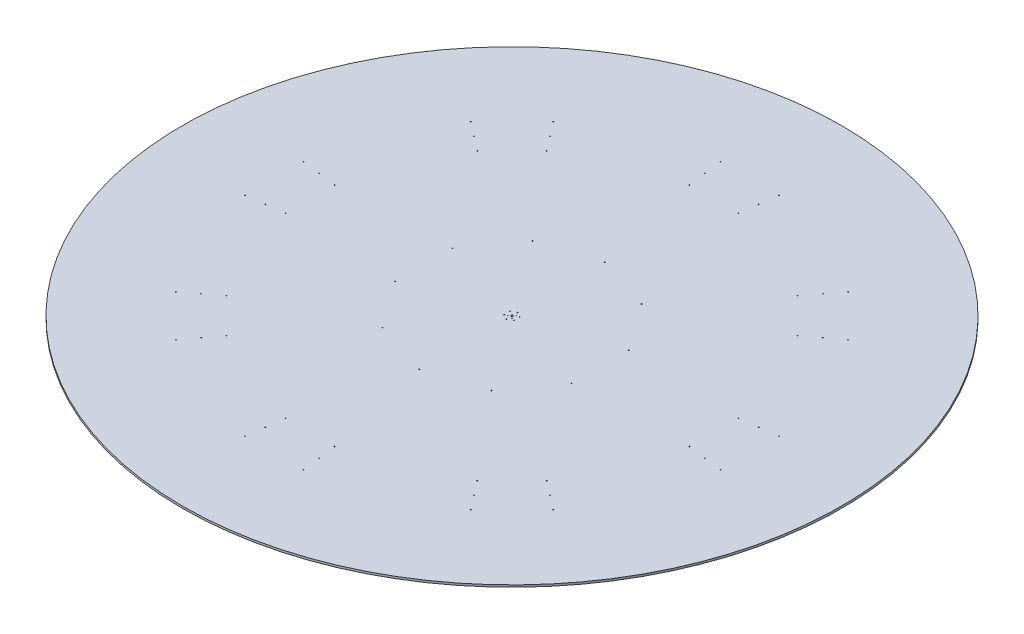
SolidWorks part; units mm, degrees
material "1060 Сплав"
ref_plane "Спереди" through (0, 0, 0) normal (0, 0, 1) x (1, 0, 0)
ref_plane "Сверху" through (0, 0, 0) normal (0, 1, 0) x (1, 0, 0)
ref_plane "Справа" through (0, 0, 0) normal (1, 0, 0) x (0, 0, -1)
sketch "Эскиз1" plane through (0, 0, 0) normal (1, 0, 0) x (0, 0, -1)
  line L0 (1600, 10) -> (5, 10)
  line L1 (1600, 0) -> (1600, 10)
  line L2 (1600, 0) -> (5, 0)
  line L3 (5, 0) -> (5, 10)
  line L4 (0, 18.0501) -> (0, -14.773) construction
  dimension "D1" = 5
  dimension "D2" = 1600
  dimension "D3" = 10
revolve "Повернуть1" add sketch "Эскиз1" angle 360 about L4
sketch "Эскиз2" plane through (0, 0, 0) normal (0, -1, 0) x (1, 0, 0)
  line L0 (0, 1753.4209) -> (0, -1955.8348) construction
  line L1 (-264.5034, 364.0576) -> (264.5034, -364.0576) construction
  line L2 (0, 450) -> (0, -450) construction
  line L3 (-427.9754, 139.0576) -> (427.9754, -139.0576) construction
  line L4 (-427.9754, -139.0576) -> (427.9754, 139.0576) construction
  line L5 (-264.5034, -364.0576) -> (264.5034, 364.0576) construction
  line L6 (23.8157, 13.75) -> (-23.8157, -13.75) construction
  line L7 (23.8157, -13.75) -> (-23.8157, 13.75) construction
  line L8 (0, -27.5) -> (0, 27.5) construction
  circle A0 centre (0, 0) radius 450 construction
  point P1 (-264.5034, 364.0576)
  point P4 (264.5034, 364.0576)
  point P5 (427.9754, 139.0576)
  point P6 (427.9754, -139.0576)
  point P7 (0, -450)
  point P8 (264.5034, -364.0576)
  point P9 (-264.5034, -364.0576)
  point P10 (-427.9754, -139.0576)
  point P11 (-427.9754, 139.0576)
  point P12 (0, 450)
  point P29 (0, 0)
  point P30 (0, 0)
  point P32 (0, 0)
  point P33 (0, 0)
  point P35 (0, 0)
  dimension "D6" = 900
  dimension "D1" = 0
  dimension "D2" = 36
  dimension "D3" = 36
  dimension "D4" = 36
  dimension "D5" = 36
  dimension "D7" = 55
  dimension "D8" = 55
  dimension "D9" = 60
  dimension "D10" = 60
  dimension "D11" = 55
hole_wizard "Отверстие обработанное метчиком M51" positions "Трехмерный эскиз1" profile "Эскиз3" tap size "M5" standard "ISO" end condition through all
sketch3d "Трехмерный эскиз1"
  point P0 (0, 0, 450)
  point P3 (264.5034, 0, 364.0576)
  point P6 (427.9754, 0, 139.0576)
  point P9 (427.9754, 0, -139.0576)
  point P12 (264.5034, 0, -364.0576)
  point P15 (0, 0, -450)
  point P18 (-264.5034, 0, -364.0576)
  point P21 (-427.9754, 0, -139.0576)
  point P24 (-427.9754, 0, 139.0576)
  point P27 (-264.5034, 0, 364.0576)
sketch "Эскиз3" plane through (0, 0, 450) normal (1, 0, 0) x (0, 0, -1)
  line L0 (0, 0) -> (0, 10)
  line L1 (0, 10) -> (2.1, 10)
  line L2 (2.1, 10) -> (2.1, 0)
  line L5 (2.1, 0) -> (0, 0)
  line L11 (0, -6.35) -> (0, 107.95) construction
  dimension "Диаметр проходного сверла" = 4.2
  dimension "Глубина проходного сверла" = 10
cosmetic thread "Отверстие резьбы1" parameters "D2"=5
cosmetic thread "Отверстие резьбы2" parameters "D2"=5
cosmetic thread "Отверстие резьбы3" parameters "D2"=5
cosmetic thread "Отверстие резьбы4" parameters "D2"=5
cosmetic thread "Отверстие резьбы5" parameters "D2"=5
cosmetic thread "Отверстие резьбы6" parameters "D2"=5
cosmetic thread "Отверстие резьбы7" parameters "D2"=5
cosmetic thread "Отверстие резьбы8" parameters "D2"=5
cosmetic thread "Отверстие резьбы9" parameters "D2"=5
cosmetic thread "Отверстие резьбы10" parameters "D2"=5
sketch "Эскиз4" plane through (0, 10, 0) normal (0, 1, 0) x (1, 0, 0)
  line L0 (0, 0) -> (0, -633.9589) construction
  line L1 (0, 0) -> (-586.754, 0) construction
  line L2 (1541.7847, 1541.7847) -> (-1541.7847, -1541.7847) construction
  line L4 (-208.8419, -1586.3118) -> (208.8419, 1586.3118) construction
  line L5 (-974.0183, -1269.3653) -> (974.0183, 1269.3653) construction
  line L10 (-163.1577, -1239.3061) -> (-117.4736, -892.3004) construction
  line L11 (-163.1577, -1239.3061) -> (-143.3288, -1241.9166) construction
  line L12 (-143.3288, -1241.9166) -> (-97.6447, -894.9109) construction
  line L13 (-97.6447, -894.9109) -> (-117.4736, -892.3004) construction
  line L14 (-153.2433, -1240.6113) -> (-107.5591, -893.6056) construction
  line L15 (-547.8853, -714.018) -> (-760.9518, -991.6917) construction
  line L16 (-760.9518, -991.6917) -> (-776.8189, -979.5164) construction
  line L17 (-776.8189, -979.5164) -> (-563.7524, -701.8428) construction
  line L18 (-563.7524, -701.8428) -> (-547.8853, -714.018) construction
  line L19 (-768.8853, -985.6041) -> (-555.8188, -707.9304) construction
  circle A1 centre (0, 0) radius 1600 construction
  point P2 (0, 0)
  point P12 (-130.4012, -1067.1085)
  point P17 (0, 0)
  point P18 (0, 0)
  point P36 (-130.4012, -1067.1085)
  point P37 (-118.9802, -980.3571)
  point P39 (-141.8222, -1153.8599)
  point P45 (-715.6187, -916.1856)
  point P46 (-662.3521, -846.7672)
  point P47 (-609.0854, -777.3488)
  dimension "D2" = 45
  dimension "D3" = 350
  dimension "D4" = 7.5
  dimension "D5" = 30
  dimension "D6" = 900
  dimension "D12" = 90
  dimension "D14" = 20
  dimension "D15" = 87.5
  dimension "D16" = 87.5
  dimension "D17" = 900
  dimension "D18" = 350
  dimension "D19" = 20
  dimension "D20" = 87.5
  dimension "D21" = 87.5
hole_wizard "Отверстие обработанное метчиком M52" positions "Эскиз5" profile "Эскиз6" tap size "M5" standard "ISO" end condition through all
sketch "Эскиз5" plane through (0, 10, 0) normal (0, 1, 0) x (1, 0, 0)
  point P0 (-118.9802, -980.3571)
  point P3 (-130.4012, -1067.1085)
  point P6 (-141.8222, -1153.8599)
  point P9 (-609.0854, -777.3488)
  point P12 (-662.3521, -846.7672)
  point P15 (-715.6187, -916.1856)
sketch "Эскиз6" plane through (-118.9802, 10, 980.3571) normal (1, 0, 0) x (0, 0, 1)
  line L0 (0, 0) -> (0, 10)
  line L1 (0, 10) -> (2.1, 10)
  line L2 (2.1, 10) -> (2.1, 0)
  line L5 (2.1, 0) -> (0, 0)
  line L11 (0, -6.35) -> (0, 107.95) construction
  dimension "Диаметр проходного сверла" = 4.2
  dimension "Глубина проходного сверла" = 10
cosmetic thread "Отверстие резьбы11" parameters "D2"=5
cosmetic thread "Отверстие резьбы12" parameters "D2"=5
cosmetic thread "Отверстие резьбы13" parameters "D2"=5
cosmetic thread "Отверстие резьбы14" parameters "D2"=5
cosmetic thread "Отверстие резьбы15" parameters "D2"=5
cosmetic thread "Отверстие резьбы16" parameters "D2"=5
pattern_circular "Круговой массив1" count 8 over 360 about axis through (0, 0, 0) along (0, 1, 0) of "Отверстие обработанное метчиком M52"
sketch "Эскиз7" plane through (0, 0, 0) normal (0, -1, 0) x (1, 0, 0)
  line L0 (0, 201753.4209) -> (0, -201955.8348) construction
  line L1 (10, 10) -> (-10, 10) construction
  line L2 (-10, 10) -> (-10, -10) construction
  line L3 (-10, -10) -> (10, -10) construction
  line L4 (10, -10) -> (10, 10) construction
  circle A0 centre (0, 0) radius 10 construction
  dimension "D1" = 90
  dimension "D2" = 20
hole_wizard "Отверстие обработанное метчиком M2.51" positions "Эскиз8" profile "Эскиз9" tap size "M2.5" standard "ISO" end condition through all
sketch "Эскиз8" plane through (0, 0, 0) normal (0, -1, 0) x (-1, 0, 0)
  point P0 (10, -10)
  point P3 (-10, -10)
  point P6 (-10, 10)
  point P9 (10, 10)
sketch "Эскиз9" plane through (-10, 0, 10) normal (1, 0, 0) x (0, 0, -1)
  line L0 (0, 0) -> (0, 10)
  line L1 (0, 10) -> (1.025, 10)
  line L2 (1.025, 10) -> (1.025, 0)
  line L5 (1.025, 0) -> (0, 0)
  line L11 (0, -6.35) -> (0, 107.95) construction
  dimension "Диаметр проходного сверла" = 2.05
  dimension "Глубина проходного сверла" = 10
cosmetic thread "Отверстие резьбы17" parameters "D2"=2.5
cosmetic thread "Отверстие резьбы18" parameters "D2"=2.5
cosmetic thread "Отверстие резьбы19" parameters "D2"=2.5
cosmetic thread "Отверстие резьбы20" parameters "D2"=2.5
hole_wizard "Отверстие обработанное метчиком M54" positions "Эскиз10" profile "Эскиз11" tap size "M5" standard "ISO"
sketch "Эскиз10" plane through (0, 10, 0) normal (0, 1, 0) x (1, 0, 0)
  point P0 (0, 27.5)
  point P3 (-23.8157, 13.75)
  point P6 (23.8157, 13.75)
  point P9 (23.8157, -13.75)
  point P12 (0, -27.5)
  point P15 (-23.8157, -13.75)
sketch "Эскиз11" plane through (0, 10, -27.5) normal (1, 0, 0) x (0, 0, 1)
  line L0 (0, 0) -> (0, 6.2618)
  line L1 (0, 6.2618) -> (2.1, 5)
  line L2 (2.1, 5) -> (2.1, 0)
  line L5 (2.1, 0) -> (0, 0)
  line L10 (0, 6.2618) -> (-2.1, 5) construction
  line L11 (0, -6.35) -> (0, 107.95) construction
  dimension "Диаметр сверла" = 4.2
  dimension "Глубина сверла" = 5
  dimension "Угол заточки сверла" = 118
cosmetic thread "Отверстие резьбы28" parameters "D1"=4.2, "D2"=5
cosmetic thread "Отверстие резьбы29" parameters "D1"=4.2, "D2"=5
cosmetic thread "Отверстие резьбы30" parameters "D1"=4.2, "D2"=5
cosmetic thread "Отверстие резьбы31" parameters "D1"=4.2, "D2"=5
cosmetic thread "Отверстие резьбы32" parameters "D1"=4.2, "D2"=5
cosmetic thread "Отверстие резьбы33" parameters "D1"=4.2, "D2"=5
